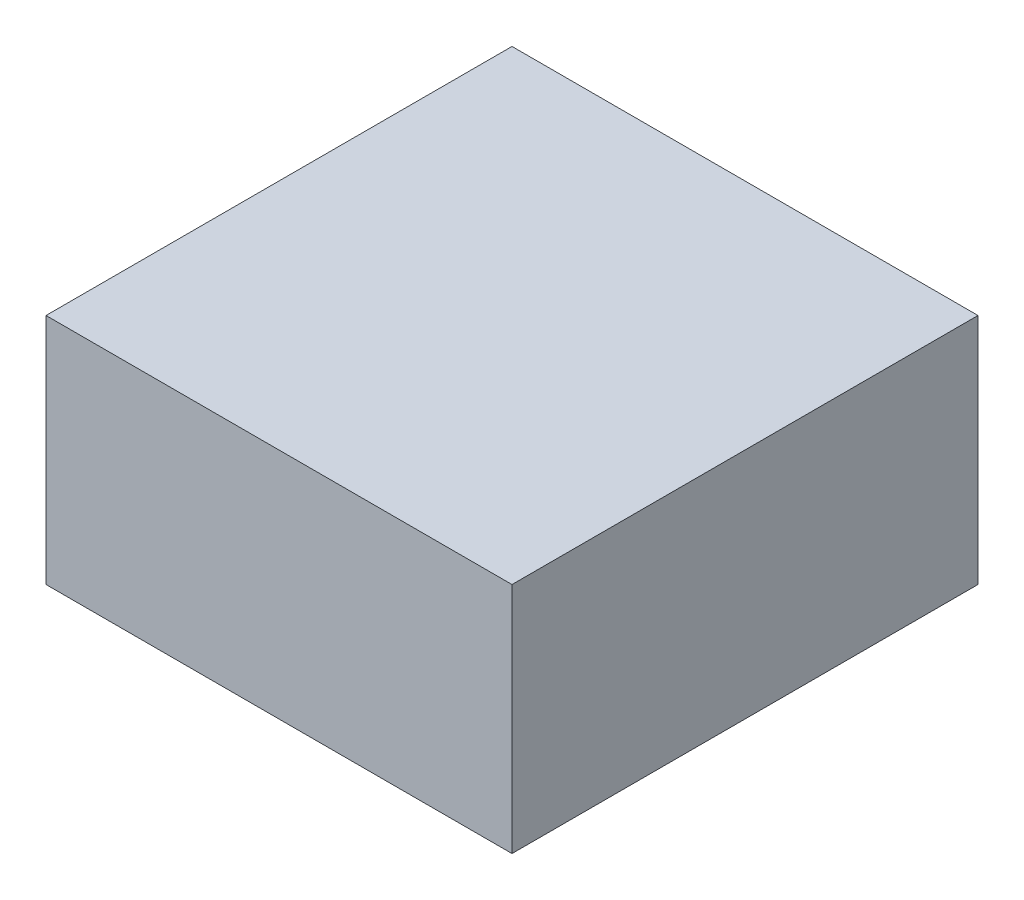
SolidWorks part; units mm, degrees
ref_plane "Front Plane" through (0, 0, 0) normal (0, 0, 1) x (1, 0, 0)
ref_plane "Top Plane" through (0, 0, 0) normal (0, 1, 0) x (1, 0, 0)
ref_plane "Right Plane" through (0, 0, 0) normal (1, 0, 0) x (0, 0, -1)
sketch "Sketch1" plane through (0, 0, 0) normal (0, 1, 0) x (1, 0, 0)
  line L1 (-34.2342, 35.6757) -> (25.7658, 35.6757)
  line L2 (-34.2342, 35.6757) -> (-34.2342, -24.3243)
  line L3 (-34.2342, -24.3243) -> (25.7658, -24.3243)
  line L4 (25.7658, 35.6757) -> (25.7658, -24.3243)
  dimension "D1" = 60
  dimension "D2" = 60
extrude "Boss-Extrude1" add sketch "Sketch1" along normal blind 30
